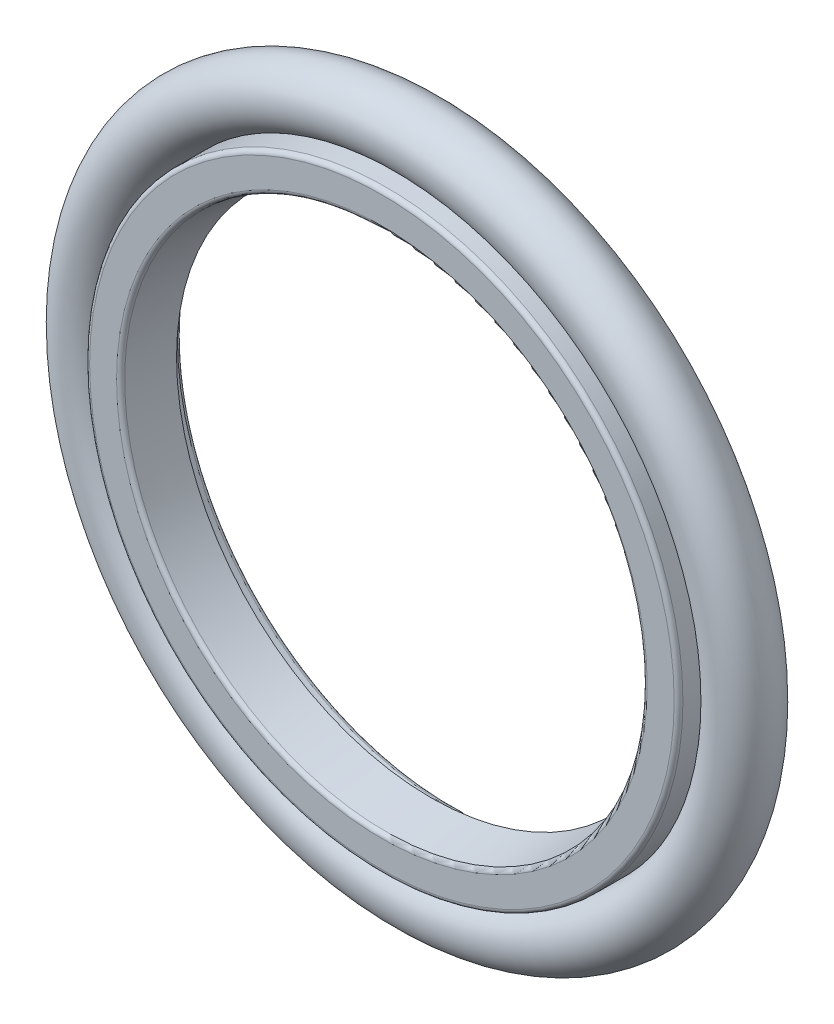
SolidWorks part; units mm, degrees
material "PTFE+NBR"
ref_plane "Front Plane" through (0, 0, 0) normal (0, 0, 1) x (1, 0, 0)
ref_plane "Top Plane" through (0, 0, 0) normal (0, 1, 0) x (1, 0, 0)
ref_plane "Right Plane" through (0, 0, 0) normal (1, 0, 0) x (0, 0, -1)
sketch "Sketch1" plane through (0, 0, 0) normal (1, 0, 0) x (0, 0, -1)
  line L0 (0, 0) -> (11.2675, 0) construction
  line L1 (0.25, 16.9) -> (3.75, 16.9)
  line L2 (0, 16.65) -> (0, 15.1168)
  line L3 (4, 16.65) -> (4, 15.65)
  line L4 (3.75, 15.4) -> (3.2, 15.4)
  line L5 (3.2, 15.4) -> (2.8, 14.5)
  line L6 (2.8, 14.5) -> (0.2146, 14.8693)
  arc A0 (0, 15.1168) -> (0.2146, 14.8693) centre (0.25, 15.1168) ccw
  arc A1 (4, 15.65) -> (3.75, 15.4) centre (3.75, 15.65) cw
  arc A2 (0.25, 16.9) -> (0, 16.65) centre (0.25, 16.65) ccw
  arc A3 (4, 16.65) -> (3.75, 16.9) centre (3.75, 16.65) ccw
  circle A4 centre (2, 18.65) radius 1.75 construction
  point P11 (0, 14.9)
  point P23 (2, 16.9)
  dimension "D8" = 0.25
  dimension "D12" = 40.8
  dimension "D13" = 3.5
  dimension "D14" = 0
  dimension "D1" = 0.8
  dimension "D2" = 1.2
  dimension "D3" = 4
  dimension "D4" = 2
  dimension "D5" = 33.8
  dimension "D6" = 2.4
  dimension "D7" = 1.5
  dimension "D9" = 29
  dimension "D10" = 29.8
  dimension "D11" = 30.8
  dimension "D15" = 29
revolve "Revolve1" add sketch "Sketch1" angle 360 about L0
sketch "Sketch2" plane through (0, 0, 0) normal (1, 0, 0) x (0, 0, -1)
  line L0 (2, 16.9) -> (2, 10.528) construction
  line L1 (3.75, 16.9) -> (0.25, 16.9) construction
  line L2 (0, 0) -> (10.3771, 0) construction
  circle A0 centre (2, 18.65) radius 1.75
  dimension "D1" = 3.5
  dimension "D2" = 40.8
revolve "Revolve2" add sketch "Sketch2" angle 360 about L2
